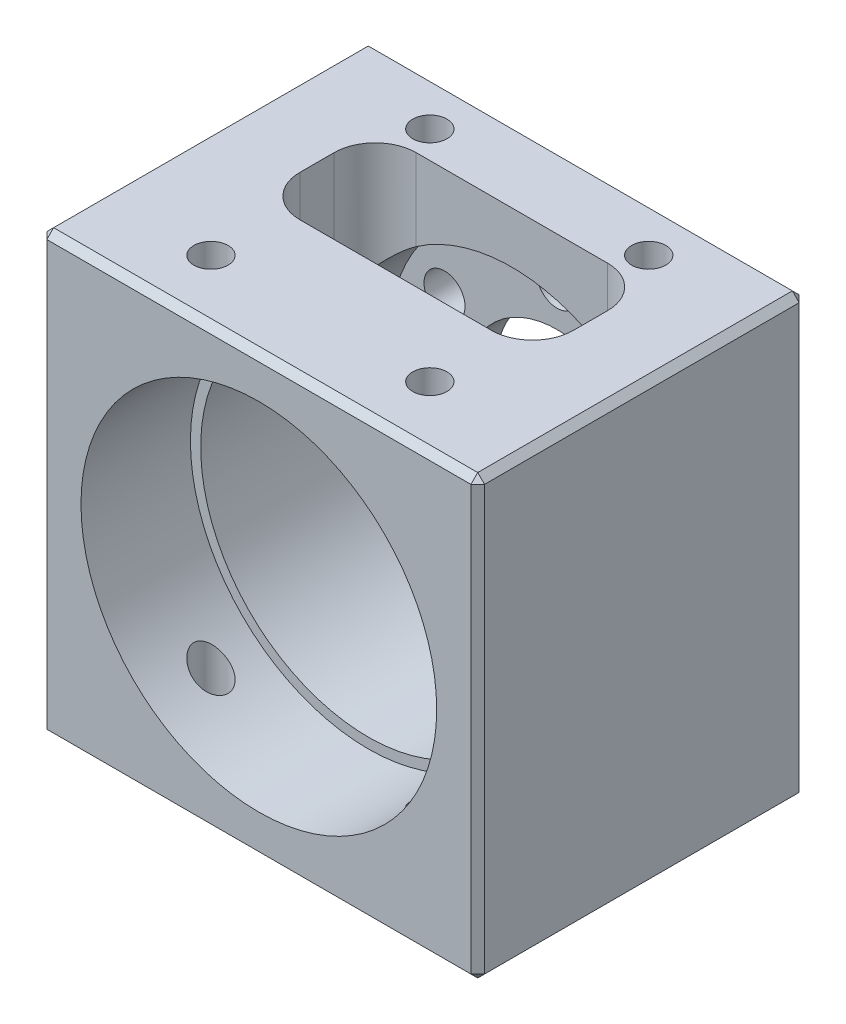
SolidWorks part; units mm, degrees
material "6061 合金"
ref_plane "前视基准面" through (0, 0, 0) normal (0, 0, 1) x (1, 0, 0)
ref_plane "上视基准面" through (0, 0, 0) normal (0, 1, 0) x (1, 0, 0)
ref_plane "右视基准面" through (0, 0, 0) normal (1, 0, 0) x (0, 0, -1)
sketch "草图1" plane through (0, 0, 0) normal (0, 0, 1) x (1, 0, 0)
  circle A0 centre (0, 0) radius 12.5 construction
  circle A1 centre (0, 0) radius 6.65
  circle A2 centre (0, 0) radius 16
  dimension "D1" = 13.3
  dimension "D2" = 25
  dimension "D3" = 32
  dimension "D4" = 3.5
extrude "凸台-拉伸1" add sketch "草图1" along normal blind 24
sketch "草图3" plane through (0, 0, 0) normal (0, 0, -1) x (-1, 0, 0)
  circle A0 centre (0, 0) radius 9.5 construction
  circle A1 centre (0, 9.5) radius 1.5
  dimension "D1" = 19
  dimension "D2" = 3
extrude "切除-拉伸2" cut sketch "草图3" against normal through all
pattern_circular "阵列(圆周)1" count 6 over 360 about axis through (0, 0, 0) along (0, 0, 1) of "切除-拉伸2"
sketch "草图4" plane through (0, 0, 24) normal (0, 0, 1) x (1, 0, 0)
  line L0 (0, 0) -> (0, -16) construction
  line L1 (-16, 0) -> (-16, -16)
  line L2 (0, 0) -> (-16, 0) construction
  line L3 (-16, -16) -> (16, -16)
  line L4 (-16, 0) -> (-16, -17.3228) construction
  line L5 (16, 16) -> (16, -16)
  line L6 (-6.65, 0) -> (-16, 0)
  line L7 (6.65, 0) -> (16, 0)
  line L8 (-16, 0) -> (-16, 16)
  line L9 (-16, 16) -> (16, 16)
  circle A0 centre (0, 0) radius 16 construction
  circle A1 centre (8.2272, -4.75) radius 1.5 construction
  circle A2 centre (0, 0) radius 6.65 construction
  arc A3 (-6.65, 0) -> (6.65, 0) centre (0, 0) ccw
  circle A4 centre (0, -9.5) radius 1.5 construction
  circle A5 centre (-8.2272, -4.75) radius 1.5 construction
  circle A6 centre (8.2272, -4.75) radius 1.5
  circle A7 centre (0, -9.5) radius 1.5
  circle A8 centre (-8.2272, -4.75) radius 1.5
  circle M5 centre (0, 0) radius 16
extrude "凸台-拉伸2" add sketch "草图4" against normal up to surface (24 mm away) contours L5 L3 M5 | L1 L3 M5 | L9 L8 M5 | L9 L5 M5 up to face at (8.9772, -3.451, 0)
sketch "草图7" plane through (0, 0, 24) normal (0, 0, 1) x (1, 0, 0)
  circle A0 centre (0, 0) radius 13
  dimension "D1" = 26
extrude "切除-拉伸3" cut sketch "草图7" against normal offset from surface (21.8 mm away) 2.2 up to face at (8.9772, -3.451, 0)
ref_plane "基准面1" through (16, -16, 0) normal (1, 0, 0) x (0, 0, -1)
sketch "草图15" plane through (0, 0, 2.2) normal (0, 0, 1) x (1, 0, 0)
  circle A0 centre (0, 0) radius 13
  circle A1 centre (0, 0) radius 12.25
  dimension "D1" = 26
  dimension "D2" = 24.5
extrude "凸台-拉伸4" add sketch "草图15" along normal offset from surface (13.8 mm away) 8 up to face at (13, 0, 24)
sketch "草图11" plane through (0, 16, 0) normal (0, 1, 0) x (1, 0, 0)
  line L0 (0, 0) -> (0, -42.9466) construction
  line L1 (16, 0) -> (-16, 0) construction
  line L2 (-16, -24) -> (16, -24) construction
  line L3 (-10, -14) -> (10, -14)
  line L4 (-10, -14) -> (-10, -5.5)
  line L5 (-10, -5.5) -> (10, -5.5)
  line L6 (10, -14) -> (10, -5.5)
  line L7 (-10, -14) -> (10, -5.5) construction
  line L8 (-10, -5.5) -> (10, -14) construction
  line L9 (16, 0) -> (16, -24) construction
  point P4 (0, -9.75)
  dimension "D1" = 5.5
  dimension "D2" = 10
  dimension "D3" = 6
extrude "切除-拉伸4" cut sketch "草图11" against normal blind 10
fillet "圆角1" radius 3 4 edges at (-10, 11.5377, 14) (10, 11.5377, 14) (10, 11.5377, 5.5) (-10, 11.5377, 5.5)
sketch "草图12" plane through (0, 16, 0) normal (0, 1, 0) x (1, 0, 0)
  line L0 (0, 17.576) -> (0, -31.2951) construction
  line L1 (16, 0) -> (-16, 0) construction
  circle A0 centre (8, -3.5) radius 1
  circle A1 centre (8, -19.5) radius 1
  circle A2 centre (-8, -3.5) radius 1
  circle A3 centre (-8, -19.5) radius 1
  dimension "D2" = 2
  dimension "D3" = 16
  dimension "D5" = 16
  dimension "D1" = 3.5
extrude "切除-拉伸5" cut sketch "草图12" against normal through all
hole_wizard "M3 螺纹孔1" positions "草图13" profile "草图14" tap size "M3" standard "GB" end condition through all
sketch "草图13" plane through (0, 16, 0) normal (0, 1, 0) x (1, 0, 0)
  point P0 (8, -3.5)
  point P3 (-8, -3.5)
  point P6 (-8, -19.5)
  point P9 (8, -19.5)
cosmetic thread "孔螺蚊线5" parameters "D2"=3
cosmetic thread "孔螺蚊线6" parameters "D2"=3
cosmetic thread "孔螺蚊线15" parameters "D2"=3
cosmetic thread "孔螺蚊线16" parameters "D2"=3
sketch "草图14" plane through (8, 16, 3.5) normal (1, 0, 0) x (0, 0, 1)
  line L0 (0, 0) -> (0, 32)
  line L1 (0, 32) -> (1.25, 32)
  line L2 (1.25, 32) -> (1.25, 0)
  line L5 (1.25, 0) -> (0, 0)
  line L11 (0, -6.35) -> (0, 107.95) construction
  dimension "通孔螺纹孔钻头直径" = 2.5
  dimension "通孔螺纹孔钻头深度" = 32
chamfer "倒角1" distance 0.5 angle 45 12 edges at (0, -16, 0) (0, -16, 24) (16, 0, 0) (16, 0, 24) (0, 16, 24) (0, 16, 0) (-16, 0, 0) (-16, 0, 24) (-16, 16, 12) (16, 16, 12) (-16, -16, 12) (16, -16, 12)
